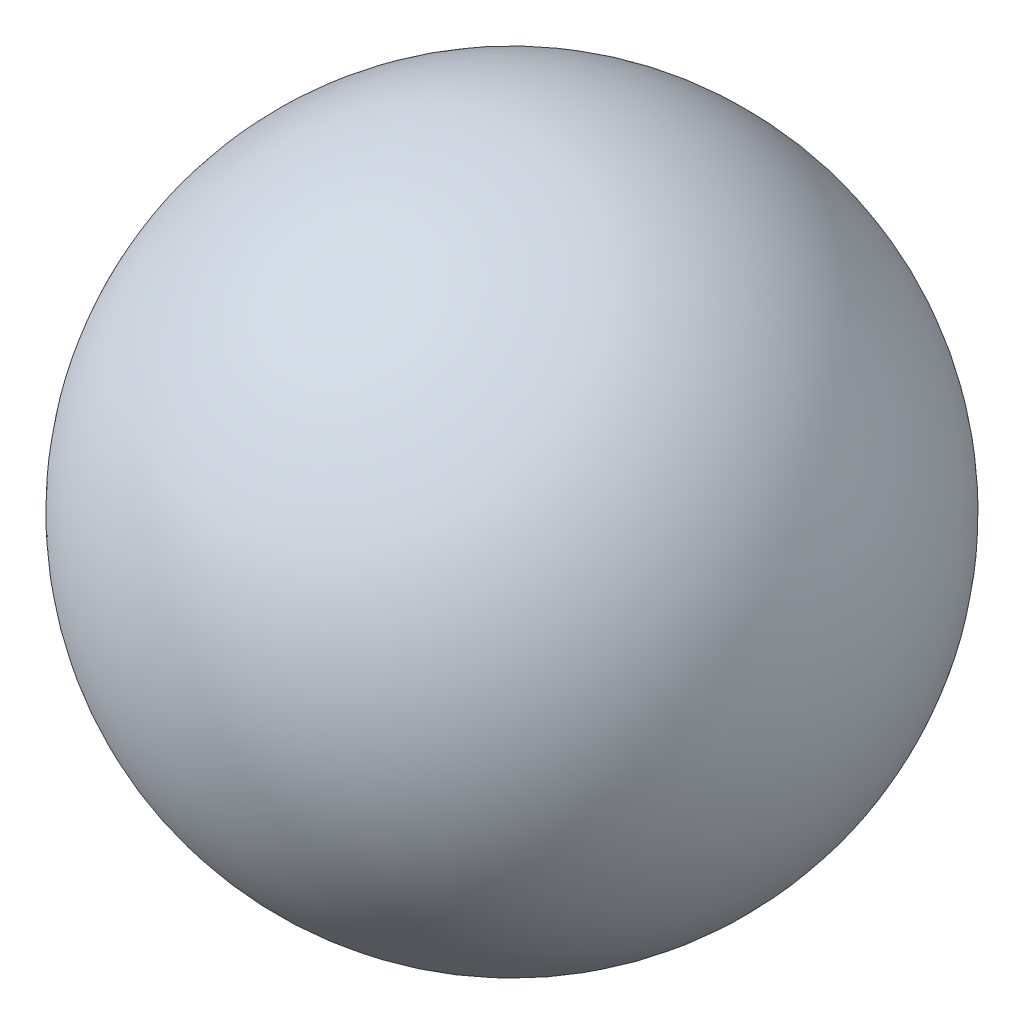
SolidWorks part; units mm, degrees
ref_plane "Plan de face" through (0, 0, 0) normal (0, 0, 1) x (1, 0, 0)
ref_plane "Plan de dessus" through (0, 0, 0) normal (0, 1, 0) x (1, 0, 0)
ref_plane "Plan de droite" through (0, 0, 0) normal (1, 0, 0) x (0, 0, -1)
sketch "Esquisse1" plane through (0, 0, 0) normal (0, 0, 1) x (1, 0, 0)
  line L0 (-2.3324, 0) -> (2.1676, 0) construction
  line L1 (-2.3324, 0) -> (2.1676, 0)
  arc A0 (-2.3324, 0) -> (2.1676, 0) centre (-0.0824, 0) cw
  dimension "D1" = 2.25
revolve "Révolution1" add sketch "Esquisse1" angle 360 about L0
